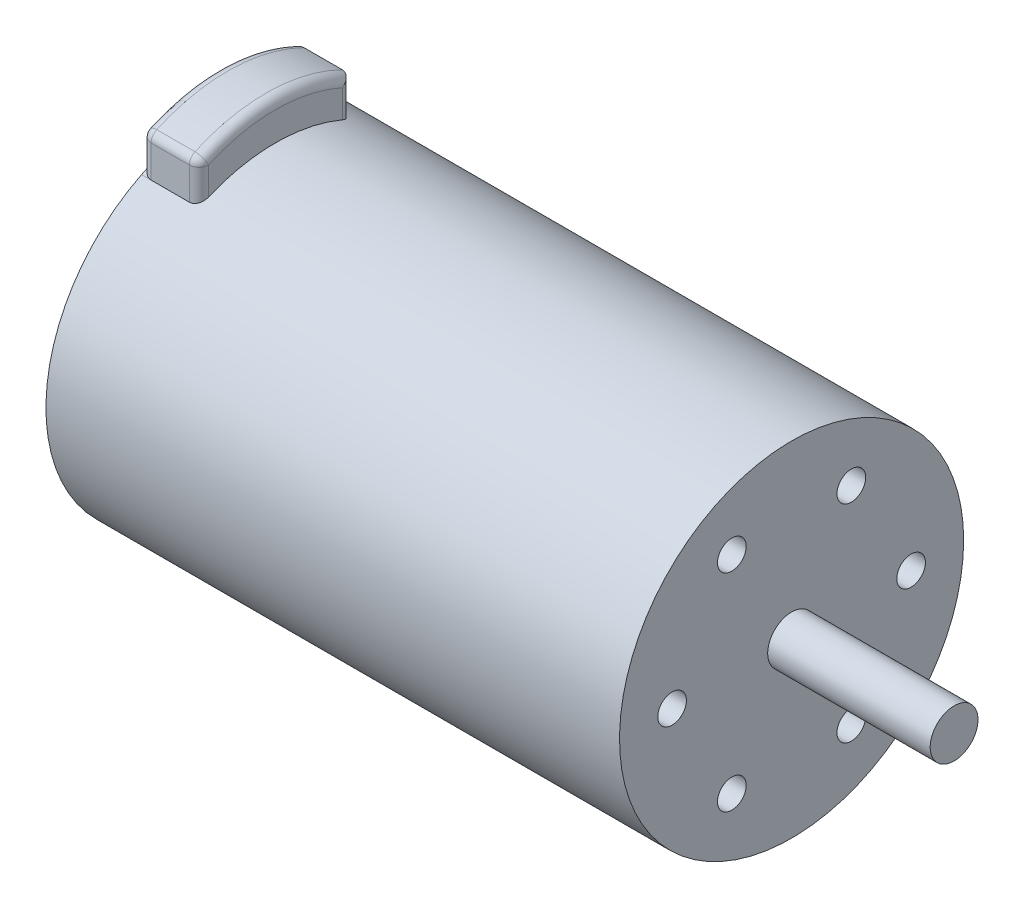
SolidWorks part; units mm, degrees
ref_plane "Front Plane" through (0, 0, 0) normal (0, 0, 1) x (1, 0, 0)
ref_plane "Top Plane" through (0, 0, 0) normal (0, 1, 0) x (1, 0, 0)
ref_plane "Right Plane" through (0, 0, 0) normal (1, 0, 0) x (0, 0, -1)
sketch "Sketch1" plane through (0, 0, 0) normal (1, 0, 0) x (0, 0, -1)
  circle A0 centre (0, 0) radius 18
  dimension "D1" = 36
extrude "Boss-Extrude1" add sketch "Sketch1" along normal blind 60
sketch "Sketch2" plane through (60, 0, 0) normal (1, 0, 0) x (0, 0, -1)
  circle A0 centre (0, 0) radius 2.5
  dimension "D1" = 5
extrude "Boss-Extrude2" add sketch "Sketch2" along normal blind 17
sketch "Sketch3" plane through (60, 0, 0) normal (1, 0, 0) x (0, 0, -1)
  circle A0 centre (0, 0) radius 12.5
  circle A1 centre (12.5, 0) radius 1.5
  circle A2 centre (6.25, -10.8253) radius 1.5
  circle A3 centre (-6.25, -10.8253) radius 1.5
  circle A4 centre (-12.5, 0) radius 1.5
  circle A5 centre (-6.25, 10.8253) radius 1.5
  circle A6 centre (6.25, 10.8253) radius 1.5
  dimension "D1" = 25
  dimension "D2" = 3
  dimension "D3" = 6
extrude "Cut-Extrude1" cut sketch "Sketch3" against normal blind 5 contours A5 | A6 | A2 | A3 | A4 | A1
sketch "Sketch4" plane through (0, 0, 0) normal (-1, 0, 0) x (0, 0, 1)
  line L0 (-8, 16.1245) -> (-8, 20.1245)
  line L1 (8, 16.1245) -> (8, 20.1245)
  arc A0 (-8, 16.1245) -> (8, 16.1245) centre (0, 0) cw
  circle A1 centre (0, 0) radius 18 construction
  arc A2 (-8, 20.1245) -> (8, 20.1245) centre (0, 4) cw
  dimension "D1" = 16
  dimension "D2" = 8
  dimension "D3" = 4
extrude "Boss-Extrude3" add sketch "Sketch4" against normal blind 6
fillet "Fillet1" radius 1 7 edges at (0, 22, 0) (6, 22, 0) (0, 18.1245, -8) (6, 18.1245, -8) (0, 18.1245, 8) (6, 18.1245, 8) (3, 20.1245, 8)
